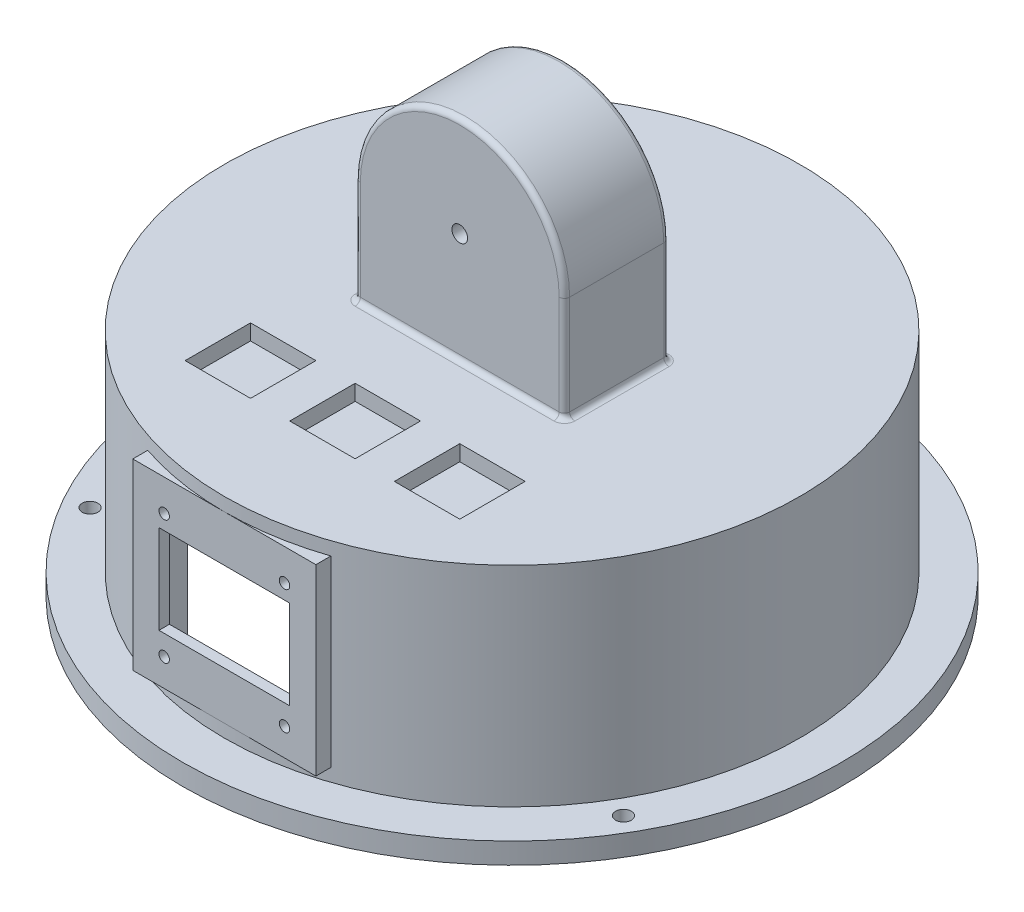
SolidWorks part; units mm, degrees
ref_plane "Front Plane" through (0, 0, 0) normal (0, 0, 1) x (1, 0, 0)
ref_plane "Top Plane" through (0, 0, 0) normal (0, 1, 0) x (1, 0, 0)
ref_plane "Right Plane" through (0, 0, 0) normal (1, 0, 0) x (0, 0, -1)
sketch "Sketch1" plane through (0, 0, 0) normal (0, 1, 0) x (1, 0, 0)
  circle A0 centre (0, 0) radius 63
  dimension "D1" = 126
extrude "Boss-Extrude4" add sketch "Sketch1" along normal blind 4
sketch "Sketch2" plane through (0, 4, 0) normal (0, 1, 0) x (1, 0, 0)
  circle A0 centre (0, 0) radius 55
  dimension "D1" = 110
extrude "Boss-Extrude5" add sketch "Sketch2" along normal blind 40
sketch "Sketch3" plane through (0, 0, 0) normal (0, -1, 0) x (1, 0, 0)
  circle A0 centre (0, 0) radius 51
  dimension "D1" = 102
extrude "Cut-Extrude1" cut sketch "Sketch3" against normal offset from surface (40 mm away) 4 up to face at (0, 44, 55)
sketch "Sketch9" plane through (0, 44, 0) normal (0, 1, 0) x (1, 0, 0)
  line L1 (20, 10) -> (-20, 10)
  line L2 (20, 10) -> (20, -10)
  line L3 (20, -10) -> (-20, -10)
  line L4 (-20, 10) -> (-20, -10)
  line L5 (20, 10) -> (-20, -10) construction
  line L6 (20, -10) -> (-20, 10) construction
  point P0 (0, 0)
  dimension "D1" = 40
  dimension "D2" = 20
extrude "Boss-Extrude8" add sketch "Sketch9" along normal blind 0.001
sketch "Sketch11" plane through (0, 0, -10) normal (0, 0, -1) x (-1, 0, 0)
  line L0 (-20, 44.001) -> (-20, 64.001)
  line L1 (20, 44.001) -> (20, 64.001)
  line L2 (-20, 44.001) -> (20, 44.001)
  arc A0 (-20, 64.001) -> (20, 64.001) centre (0, 64.001) cw
  point P8 (0, 44.001)
  dimension "D1" = 20
extrude "Boss-Extrude9" add sketch "Sketch11" against normal up to surface (20 mm away) up to face at (0, 44.0005, 10)
sketch "Sketch12" plane through (0, 0, 10) normal (0, 0, 1) x (1, 0, 0)
  circle A0 centre (0, 65) radius 1.5
  dimension "D1" = 3
  dimension "D2" = 65
extrude "Cut-Extrude4" cut sketch "Sketch12" against normal up to surface (20 mm away) up to face at (0, 59.0005, -10)
ref_plane "Plane4" through (0, 0, 55) normal (0, 0, 1) x (1, 0, 0)
sketch "Sketch22" plane through (0, 0, 55) normal (0, 0, 1) x (1, 0, 0)
  line L1 (17.5, 41.4716) -> (-17.5, 41.4716)
  line L2 (17.5, 41.4716) -> (17.5, 6.4716)
  line L3 (17.5, 6.4716) -> (-17.5, 6.4716)
  line L4 (-17.5, 41.4716) -> (-17.5, 6.4716)
  line L5 (17.5, 41.4716) -> (-17.5, 6.4716) construction
  line L6 (17.5, 6.4716) -> (-17.5, 41.4716) construction
  point P0 (0, 23.9716)
  dimension "D1" = 35
  dimension "D2" = 35
ref_plane "Plane6" through (0, 0, 46) normal (0, 0, 1) x (1, 0, 0)
extrude "Boss-Extrude10" add sketch "Sketch22" against normal up to surface (9 mm away)
sketch "Sketch24" plane through (0, 0, 46) normal (0, 0, -1) x (-1, 0, 0)
  line L1 (-16, 39.7226) -> (16, 39.7226)
  line L2 (-16, 39.7226) -> (-16, 7.7226)
  line L3 (-16, 7.7226) -> (16, 7.7226)
  line L4 (16, 39.7226) -> (16, 7.7226)
  line L5 (-16, 39.7226) -> (16, 7.7226) construction
  line L6 (-16, 7.7226) -> (16, 39.7226) construction
  point P0 (0, 23.7226)
  dimension "D1" = 32
  dimension "D2" = 32
extrude "Cut-Extrude15" cut sketch "Sketch24" against normal offset from surface (7 mm away) 2 up to face at (0, 23.9716, 55)
sketch "Sketch25" plane through (0, 0, 55) normal (0, 0, 1) x (1, 0, 0)
  line L1 (-12.5, 32.6006) -> (12.5, 32.6006)
  line L2 (-12.5, 32.6006) -> (-12.5, 15.6006)
  line L3 (-12.5, 15.6006) -> (12.5, 15.6006)
  line L4 (12.5, 32.6006) -> (12.5, 15.6006)
  line L5 (-12.5, 32.6006) -> (12.5, 15.6006) construction
  line L6 (-12.5, 15.6006) -> (12.5, 32.6006) construction
  point P0 (0, 24.1006)
  dimension "D1" = 17
  dimension "D2" = 25
fillet "Fillet6" radius 1 10 edges at (-20, 44, 0) (0, 44, 10) (0, 44, -10) (-20, 54.0005, -10) (0, 84.001, 10) (0, 84.001, -10) (20, 54.0005, 10) (-20, 54.0005, 10) (20, 44, 0) (20, 54.0005, -10)
extrude "Cut-Extrude16" cut sketch "Sketch25" against normal up to surface (2 mm away) up to face at (0, 23.7226, 53)
sketch "Sketch26" plane through (0, 0, 55) normal (0, 0, 1) x (1, 0, 0)
  circle A0 centre (-11.5, 35.429) radius 1
  circle A1 centre (11.5, 35.429) radius 1
  circle A2 centre (11.5, 11.7276) radius 1
  circle A3 centre (-11.5, 11.7276) radius 1
  dimension "D4" = 2
  dimension "D1" = 3
  dimension "D2" = 3
  dimension "D3" = 23
  dimension "D5" = 4
extrude "Cut-Extrude18" cut sketch "Sketch26" against normal up to surface (2 mm away) up to face at (0, 23.7226, 53)
sketch "Sketch29" plane through (0, 4, 0) normal (0, 1, 0) x (1, 0, 0)
  circle A0 centre (0, 59) radius 1.5
  circle A1 centre (-50.986, -29.6889) radius 1.5
  circle A2 centre (50.986, -29.6889) radius 1.5
  dimension "D2" = 3
  dimension "D1" = 59
  dimension "D3" = 59
  dimension "D4" = 59
  dimension "D5" = 102.3
  dimension "D6" = 102.3
sketch "Sketch30" plane through (0, 44, 0) normal (0, 1, 0) x (1, 0, 0)
  line L1 (26.25, -36.25) -> (13.75, -36.25)
  line L2 (26.25, -36.25) -> (26.25, -23.75)
  line L3 (26.25, -23.75) -> (13.75, -23.75)
  line L4 (13.75, -36.25) -> (13.75, -23.75)
  line L5 (26.25, -36.25) -> (13.75, -23.75) construction
  line L6 (26.25, -23.75) -> (13.75, -36.25) construction
  line L7 (6.25, -23.75) -> (-6.25, -23.75)
  line L8 (6.25, -23.75) -> (6.25, -36.25)
  line L9 (6.25, -36.25) -> (-6.25, -36.25)
  line L10 (-6.25, -23.75) -> (-6.25, -36.25)
  line L11 (6.25, -23.75) -> (-6.25, -36.25) construction
  line L12 (6.25, -36.25) -> (-6.25, -23.75) construction
  line L13 (-13.75, -23.75) -> (-26.25, -23.75)
  line L14 (-13.75, -23.75) -> (-13.75, -36.25)
  line L15 (-13.75, -36.25) -> (-26.25, -36.25)
  line L16 (-26.25, -23.75) -> (-26.25, -36.25)
  line L17 (-13.75, -23.75) -> (-26.25, -36.25) construction
  line L18 (-13.75, -36.25) -> (-26.25, -23.75) construction
  point P0 (20, -30)
  point P5 (0, -30)
  point P10 (-20, -30)
  dimension "D1" = 20
  dimension "D2" = 40
  dimension "D3" = 30
  dimension "D4" = 12.5
extrude "Cut-Extrude24" cut sketch "Sketch30" against normal offset from surface (3 mm away) 1 up to face at (0, 40, 22.2259)
extrude "Cut-Extrude25" cut sketch "Sketch29" against normal up to surface (4 mm away) up to face at (0, 0, -51)
